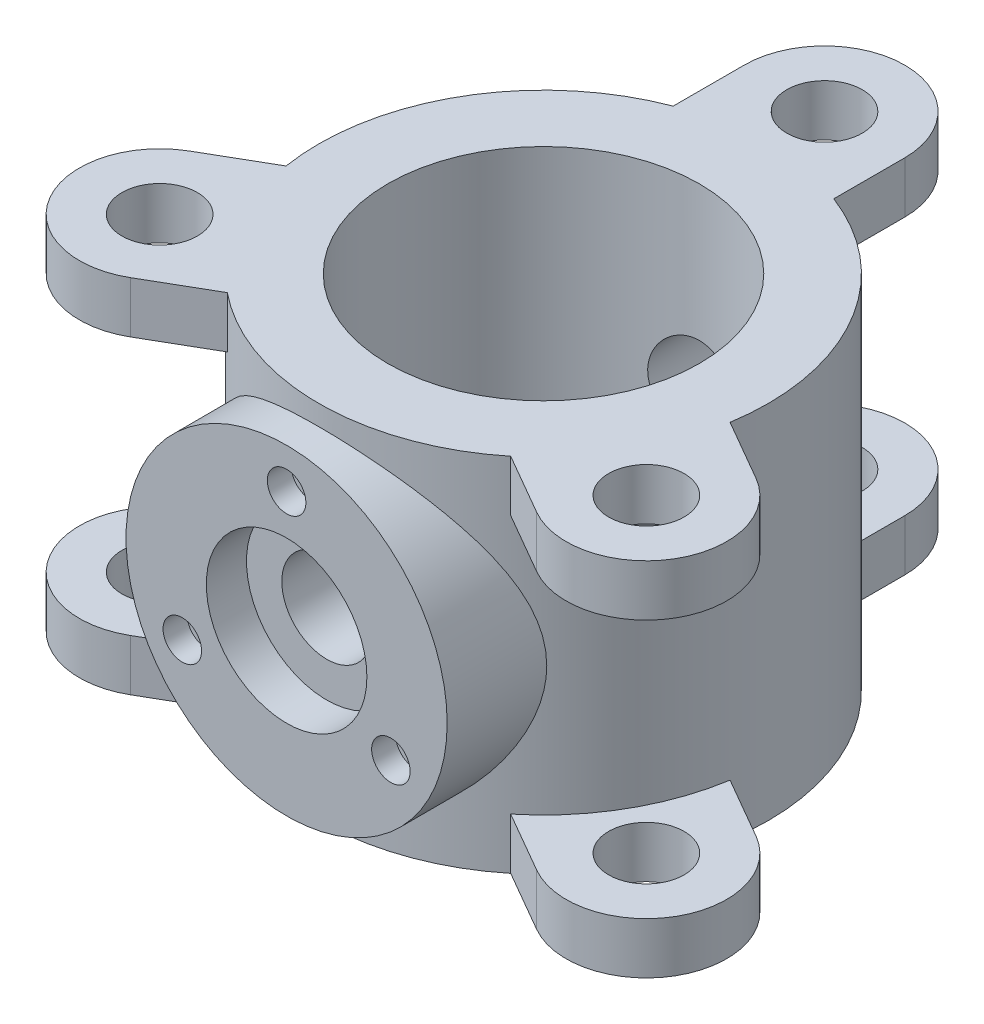
SolidWorks part; units mm, degrees
ref_plane "Front Plane" through (0, 0, 0) normal (0, 0, 1) x (1, 0, 0)
ref_plane "Top Plane" through (0, 0, 0) normal (0, 1, 0) x (1, 0, 0)
ref_plane "Right Plane" through (0, 0, 0) normal (1, 0, 0) x (0, 0, -1)
sketch "Sketch1" plane through (0, 0, 0) normal (0, 1, 0) x (1, 0, 0)
  circle A0 centre (0, 0) radius 140
  circle A1 centre (0, 0) radius 97
  dimension "D1" = 280
  dimension "D2" = 194
extrude "Boss-Extrude1" add sketch "Sketch1" along normal blind 225
sketch "Sketch2" plane through (0, 225, 0) normal (0, 1, 0) x (1, 0, 0)
  line L2 (-50, 175) -> (-50, 107.6368)
  line L3 (-50, 107.6368) -> (50, 107.6368)
  line L4 (50, 175) -> (50, 107.6368)
  line L5 (-50, 175) -> (50, 107.6368) construction
  line L6 (-50, 107.6368) -> (50, 175) construction
  arc A0 (50, 175) -> (-50, 175) centre (0, 175) ccw
  circle A1 centre (0, 175) radius 23.5
  point P0 (0, 141.3184)
  dimension "D2" = 100
  dimension "D3" = 47
  dimension "D1" = 175
extrude "Boss-Extrude2" add sketch "Sketch2" against normal blind 32
pattern_circular "CirPattern1" count 3 over 360 about axis through (0, 0, 0) along (0, 1, 0) of "Boss-Extrude2"
ref_plane "Plane1" through (0, 112.5, 0) normal (0, 1, 0) x (1, 0, 0)
mirror "Mirror1" about plane through (0, 112.5, 0) normal (0, 1, 0) of "CirPattern1", "Boss-Extrude2"
ref_plane "Plane2" through (0, 0, 160) normal (0, 0, 1) x (1, 0, 0)
sketch "Sketch3" plane through (0, 0, 160) normal (0, 0, 1) x (1, 0, 0)
  circle A0 centre (0, 112.5) radius 100
  dimension "D1" = 200
  dimension "D2" = 112.5
extrude "Boss-Extrude4" add sketch "Sketch3" against normal up to next contours A0
sketch "Sketch5" plane through (0, 0, 160) normal (0, 0, 1) x (1, 0, 0)
  circle A0 centre (0, 112.5) radius 50
  dimension "D1" = 100
extrude "Cut-Extrude1" cut sketch "Sketch5" against normal blind 25
sketch "Sketch6" plane through (0, 0, 135) normal (0, 0, 1) x (1, 0, 0)
  circle A0 centre (0, 112.5) radius 28
  dimension "D1" = 56
extrude "Cut-Extrude2" cut sketch "Sketch6" against normal through all
sketch "Sketch7" plane through (0, 0, 160) normal (0, 0, 1) x (1, 0, 0)
  circle A0 centre (0, 187.5) radius 12
  circle A1 centre (0, 112.5) radius 28 construction
  dimension "D1" = 24
  dimension "D2" = 75
extrude "Cut-Extrude3" cut sketch "Sketch7" against normal blind 15
pattern_circular "CirPattern2" count 3 over 360 about axis through (0, 112.5, 0) along (0, 0, 1) of "Cut-Extrude3"
